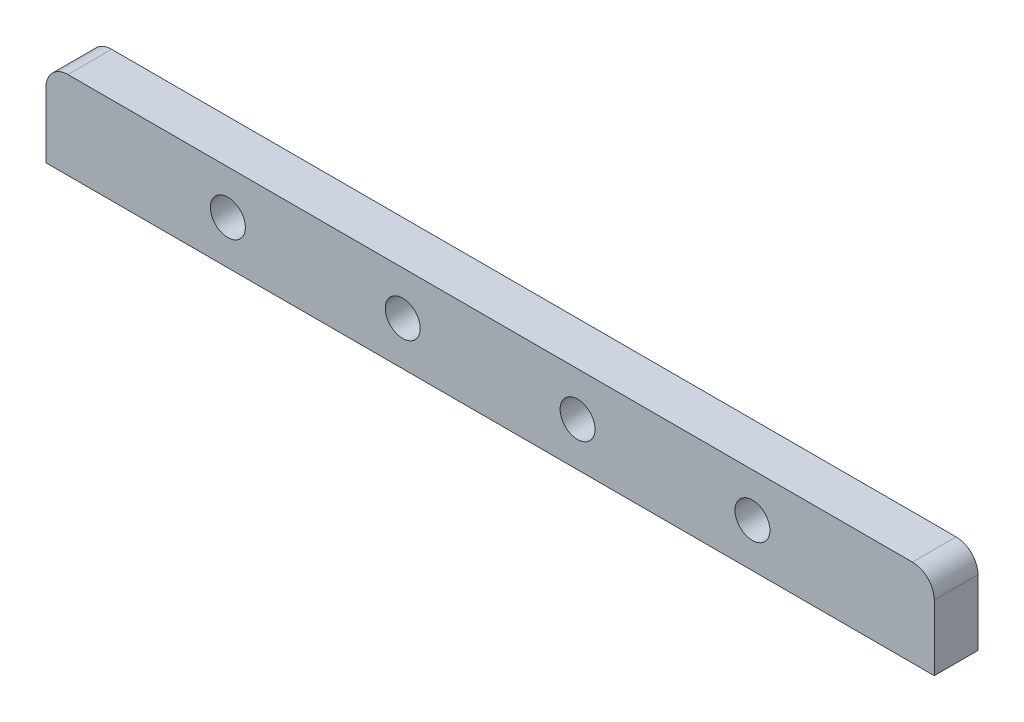
SolidWorks part; units mm, degrees
ref_plane "Front Plane" through (0, 0, 0) normal (0, 0, 1) x (1, 0, 0)
ref_plane "Top Plane" through (0, 0, 0) normal (0, 1, 0) x (1, 0, 0)
ref_plane "Right Plane" through (0, 0, 0) normal (1, 0, 0) x (0, 0, -1)
sketch "Sketch1" plane through (0, 0, 0) normal (0, 0, 1) x (1, 0, 0)
  line L0 (0, 0) -> (0, 49.3537) construction
  line L1 (-50.8, 0) -> (50.8, 0)
  line L2 (-50.8, 0) -> (-50.8, 10)
  line L3 (-50.8, 10) -> (50.8, 10)
  line L4 (50.8, 0) -> (50.8, 10)
  dimension "D1" = 101.6
  dimension "D2" = 10
extrude "Boss-Extrude1" add sketch "Sketch1" along normal blind 5 contours L2 L3 L4 L1
sketch "Sketch2" plane through (0, 0, 5) normal (0, 0, 1) x (1, 0, 0)
  line L0 (50.8, 5) -> (-57.0494, 5) construction
  line L1 (50.8, 0) -> (50.8, 10) construction
  line L2 (-30, 5) -> (-10, 5) construction
  circle A0 centre (-30, 5) radius 2
  circle A1 centre (-10, 5) radius 2
  circle A2 centre (10, 5) radius 2
  circle A3 centre (30, 5) radius 2
  dimension "D1" = 4
  dimension "D2" = 20
  dimension "D3" = 10
extrude "Cut-Extrude1" cut sketch "Sketch2" against normal up to surface (5 mm away) up to face at (0, 5, 0)
fillet "Fillet1" radius 2.5 2 edges at (50.8, 10, 2.5) (-50.8, 10, 2.5)
